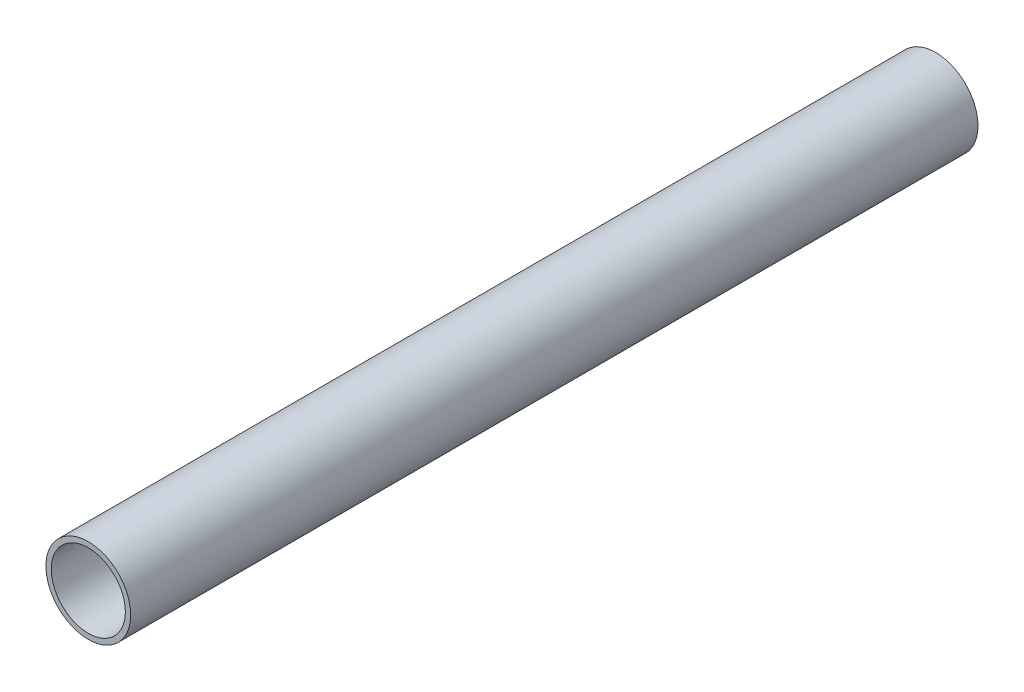
SolidWorks part; units mm, degrees
ref_plane "Front Plane" through (0, 0, 0) normal (0, 0, 1) x (1, 0, 0)
ref_plane "Top Plane" through (0, 0, 0) normal (0, 1, 0) x (1, 0, 0)
ref_plane "Right Plane" through (0, 0, 0) normal (1, 0, 0) x (0, 0, -1)
sketch "Sketch1" plane through (0, 0, 0) normal (0, 0, 1) x (1, 0, 0)
  circle A0 centre (0, 0) radius 7
  circle A1 centre (0, 0) radius 8
  dimension "D1" = 16
  dimension "D2" = 14
extrude "Boss-Extrude1" add sketch "Sketch1" along normal blind 160
